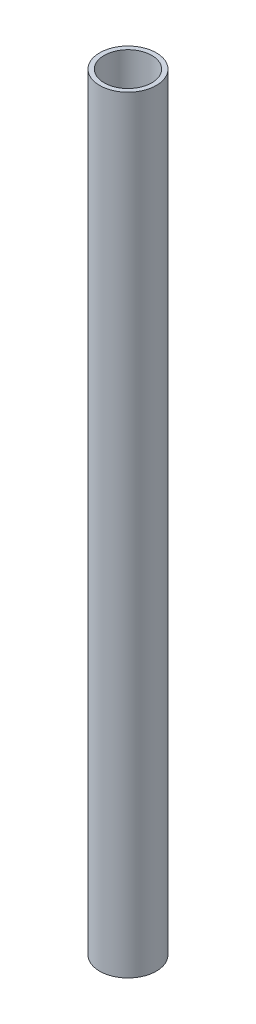
SolidWorks part; units mm, degrees
ref_plane "Front Plane" through (0, 0, 0) normal (0, 0, 1) x (1, 0, 0)
ref_plane "Top Plane" through (0, 0, 0) normal (0, 1, 0) x (1, 0, 0)
ref_plane "Right Plane" through (0, 0, 0) normal (1, 0, 0) x (0, 0, -1)
sketch "Sketch1" plane through (0, 0, 0) normal (0, 1, 0) x (1, 0, 0)
  circle A0 centre (0, 0) radius 0.535
  circle A1 centre (0, 0) radius 0.45
  dimension "D1" = 1.07
  dimension "D2" = 0.9
extrude "Boss-Extrude1" add sketch "Sketch1" along normal blind 14.5
